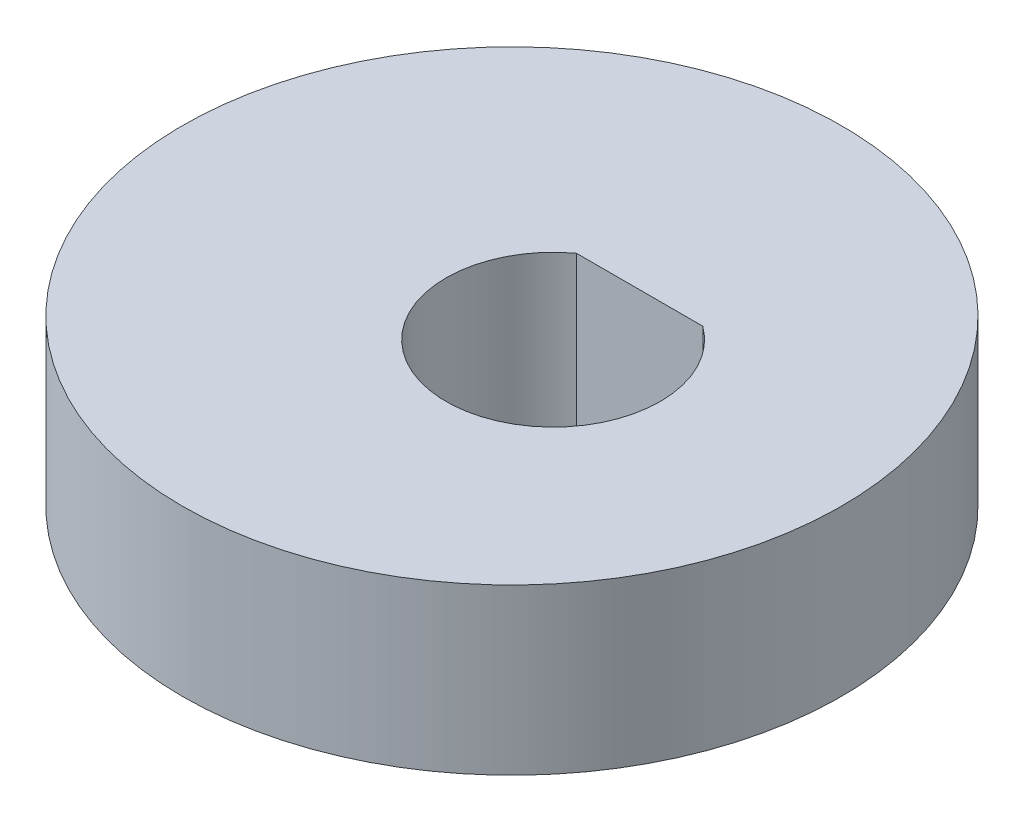
SolidWorks part; units mm, degrees
ref_plane "Front Plane" through (0, 0, 0) normal (0, 0, 1) x (1, 0, 0)
ref_plane "Top Plane" through (0, 0, 0) normal (0, 1, 0) x (1, 0, 0)
ref_plane "Right Plane" through (0, 0, 0) normal (1, 0, 0) x (0, 0, -1)
sketch "Sketch1" plane through (0, 0, 0) normal (0, 1, 0) x (1, 0, 0)
  line L0 (-0.533, 2.1) -> (2.533, 2.1)
  circle A0 centre (1, 0) radius 2.6
  circle A1 centre (0, 0) radius 8
  dimension "D1" = 5.2
  dimension "D4" = 16
  dimension "D2" = 2.1
  dimension "D3" = 1
extrude "Boss-Extrude1" add sketch "Sketch1" along normal blind 4 contours A1 A0 | L0 A0
